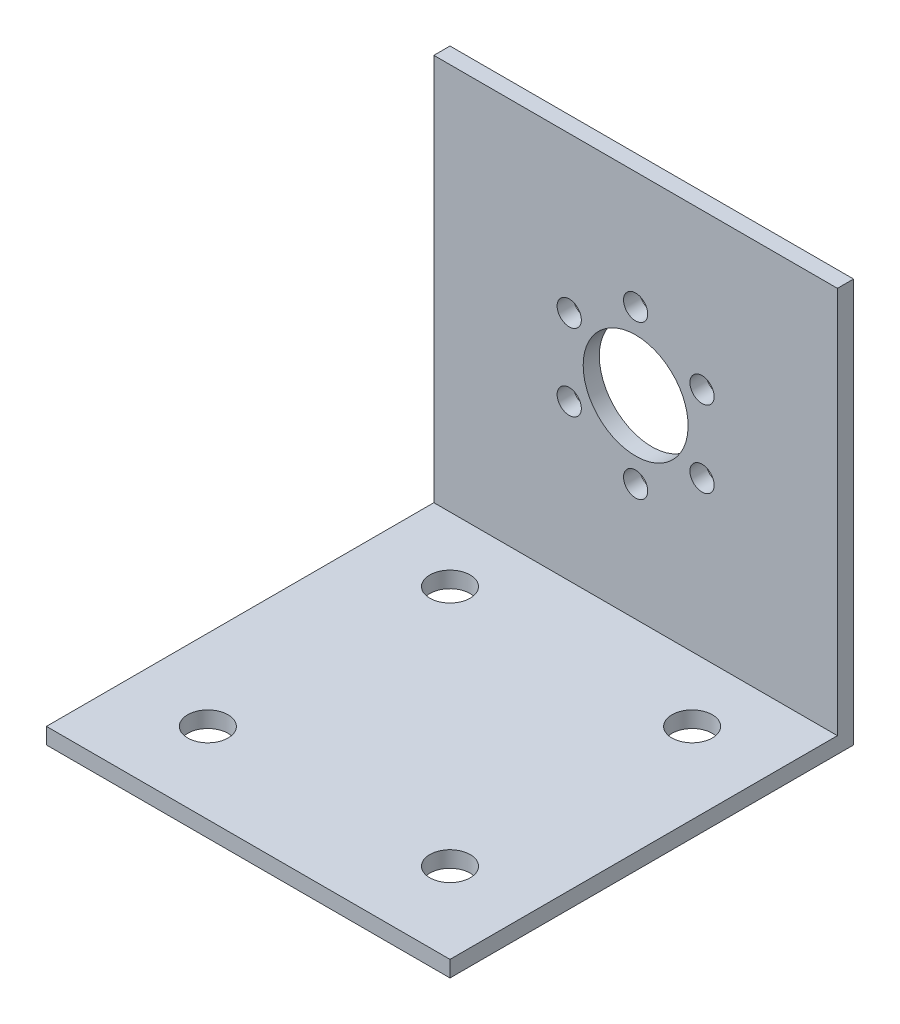
SolidWorks part; units mm, degrees
ref_plane "前视基准面" through (0, 0, 0) normal (0, 0, 1) x (1, 0, 0)
ref_plane "上视基准面" through (0, 0, 0) normal (0, 1, 0) x (1, 0, 0)
ref_plane "右视基准面" through (0, 0, 0) normal (1, 0, 0) x (0, 0, -1)
other "Configuration Table"
sketch "草图2" plane through (0, 0, 0) normal (1, 0, 0) x (0, 0, -1)
  line L0 (0, 0) -> (50, 0)
  line L1 (50, 0) -> (50, 50)
  line L2 (50, 50) -> (48, 50)
  line L3 (48, 50) -> (48, 2)
  line L4 (48, 2) -> (0, 2)
  line L5 (0, 2) -> (0, 0)
  dimension "D1" = 50
  dimension "D2" = 50
  dimension "D3" = 2
  dimension "D4" = 2
extrude "凸台-拉伸1" add sketch "草图2" along normal blind 50
sketch "草图3" plane through (0, 0, -50) normal (0, 0, -1) x (-1, 0, 0)
  line L0 (0, 0) -> (0, 50) construction
  line L1 (-50, 0) -> (0, 0) construction
  line L2 (-25, 35.5) -> (-25, 26) construction
  line L3 (-25, 26) -> (-16.7728, 30.75) construction
  circle A0 centre (-25, 26) radius 6.5
  circle A1 centre (-25, 35.5) radius 1.5
  circle A2 centre (-16.7728, 30.75) radius 1.5
  circle A3 centre (-16.7728, 21.25) radius 1.5
  circle A4 centre (-25, 16.5) radius 1.5
  circle A5 centre (-33.2272, 21.25) radius 1.5
  circle A6 centre (-33.2272, 30.75) radius 1.5
  point P21 (-25, 26)
  dimension "D1" = 13
  dimension "D4" = 3
  dimension "D2" = 25
  dimension "D3" = 26
  dimension "D5" = 9.5
  dimension "D7" = 60
  dimension "D8" = 9.5
  dimension "D6" = 6
extrude "切除-拉伸1" cut sketch "草图3" against normal blind 50
sketch "草图4" plane through (0, 0, 0) normal (0, -1, 0) x (1, 0, 0)
  line L0 (10, -10) -> (40, -10) construction
  line L1 (40, -10) -> (40, -40) construction
  line L2 (40, -40) -> (10, -40) construction
  line L3 (10, -40) -> (10, -10) construction
  line L4 (50, 0) -> (50, -50) construction
  line L5 (50, 0) -> (0, 0) construction
  circle A0 centre (10, -10) radius 2.5
  circle A1 centre (40, -10) radius 2.5
  circle A2 centre (10, -40) radius 2.5
  circle A3 centre (40, -40) radius 2.5
  dimension "D3" = 5
  dimension "D1" = 30
  dimension "D2" = 30
  dimension "D4" = 10
  dimension "D5" = 10
extrude "切除-拉伸2" cut sketch "草图4" against normal blind 50
